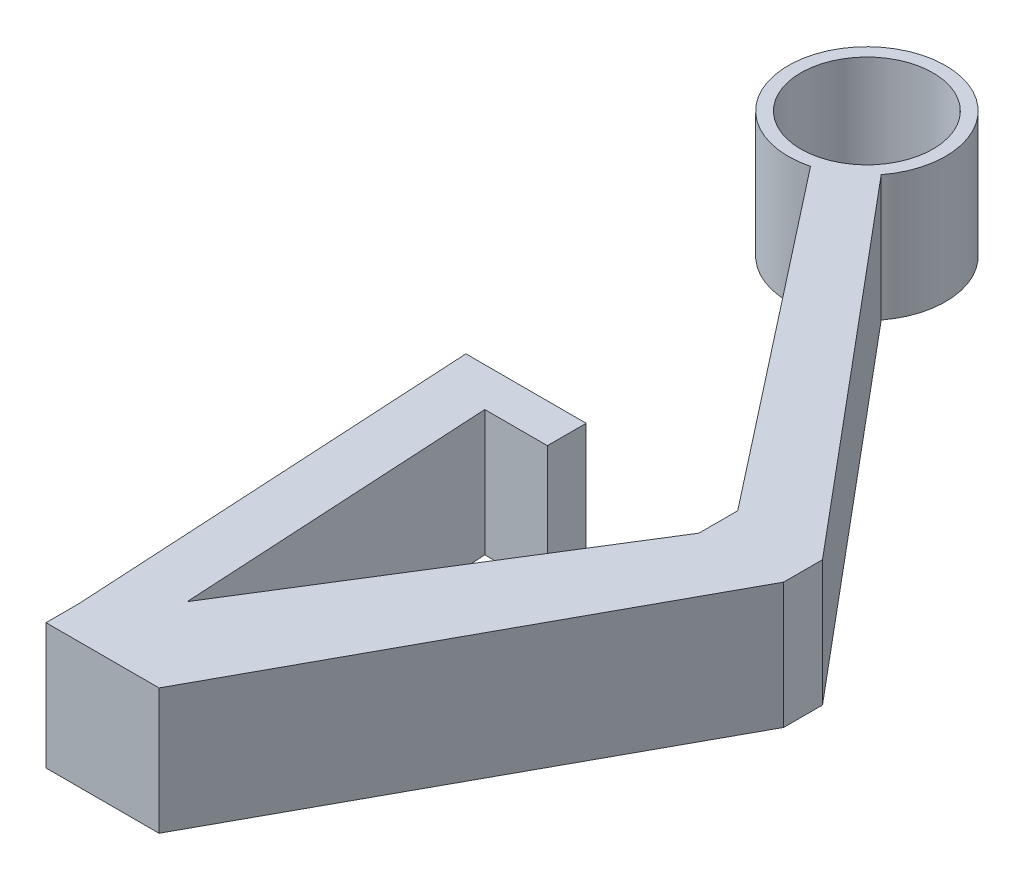
SolidWorks part; units mm, degrees
ref_plane "Front Plane" through (0, 0, 0) normal (0, 0, 1) x (1, 0, 0)
ref_plane "Top Plane" through (0, 0, 0) normal (0, 1, 0) x (1, 0, 0)
ref_plane "Right Plane" through (0, 0, 0) normal (1, 0, 0) x (0, 0, -1)
sketch "Sketch1" plane through (0, 0, 0) normal (0, 1, 0) x (1, 0, 0)
  circle A0 centre (0, 0) radius 0.42
  circle A1 centre (0, 0) radius 0.5
  dimension "D1" = 0.84
extrude "Boss-Extrude1" add sketch "Sketch1" along normal blind 0.8
sketch "Sketch2" plane through (0, 0, 0) normal (0, 1, 0) x (1, 0, 0)
  line L0 (0.1083, -0.4617) -> (1.7897, -2.6106)
  line L1 (1.7897, -2.6106) -> (1.7897, -2.857)
  line L2 (1.7897, -2.857) -> (0.5406, -4.8605)
  line L3 (0.5406, -4.8605) -> (0.429, -2.857)
  line L4 (0.429, -2.857) -> (0.8268, -2.857)
  line L5 (0.8268, -2.857) -> (0.8268, -2.6106)
  line L6 (0.8268, -2.6106) -> (0.0625, -2.6106)
  line L7 (0.0625, -2.6106) -> (0.2078, -5.2182)
  line L8 (0.2078, -5.2182) -> (0.2078, -5.4241)
  line L9 (0.2078, -5.4241) -> (0.9261, -5.4241)
  line L10 (0.9261, -5.4241) -> (2.3283, -2.857)
  line L11 (2.3283, -2.857) -> (2.3283, -2.6106)
  line L12 (2.3283, -2.6106) -> (0.3961, -0.3052)
  line L13 (0.3961, -0.3052) -> (0.1083, -0.4617)
  circle A0 centre (0, 0) radius 0.5 construction
  point P8 (0.3961, -0.3052)
  point P17 (0.1083, -0.4617)
extrude "Boss-Extrude2" add sketch "Sketch2" along normal blind 0.8
